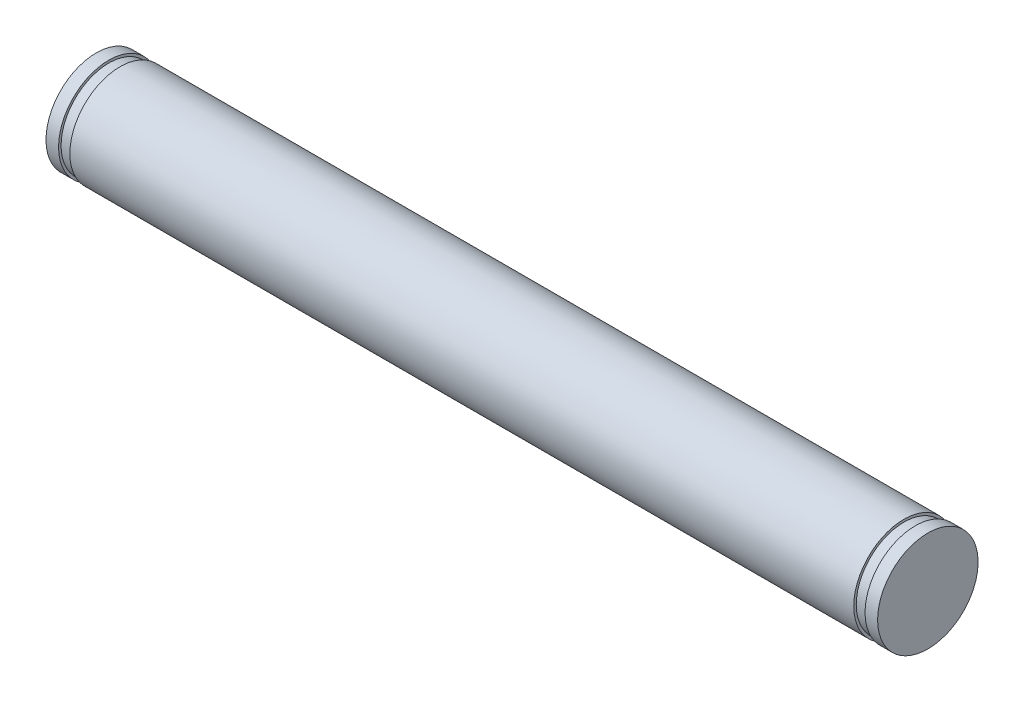
SolidWorks part; units mm, degrees
material "1060 Alloy"
ref_plane "Front Plane" through (0, 0, 0) normal (0, 0, 1) x (1, 0, 0)
ref_plane "Top Plane" through (0, 0, 0) normal (0, 1, 0) x (1, 0, 0)
ref_plane "Right Plane" through (0, 0, 0) normal (1, 0, 0) x (0, 0, -1)
sketch "Sketch1" plane through (0, 0, 0) normal (0, 0, 1) x (1, 0, 0)
  line L0 (62.4, 3.8) -> (63.3, 3.8)
  line L1 (0, 0) -> (62.4, 0)
  line L2 (0, 3.8) -> (0, 4)
  line L3 (0, 4) -> (62.4, 4)
  line L4 (62.4, 1.6806) -> (62.4, 1.7815)
  line L5 (63.3, 3.8) -> (63.3, 4)
  line L6 (63.3, 4) -> (64.3, 4)
  line L7 (64.3, 4) -> (64.3, 0)
  line L8 (62.4, 0) -> (64.3, 0)
  line L9 (62.4, 0) -> (64.3, 0)
  line L10 (62.1234, 1.7815) -> (62.4, 1.7815)
  line L11 (62.4, 1.6806) -> (62.1234, 1.7815)
  line L12 (62.4, 3.8) -> (62.4, 4)
  line L13 (0, 3.8) -> (-0.9, 3.8)
  line L14 (-0.9, 3.8) -> (-0.9, 4)
  line L15 (-0.9, 4) -> (-1.9, 4)
  line L16 (-1.9, 4) -> (-1.9, 0)
  line L17 (-1.9, 0) -> (0, 0)
  line L18 (-1.9, 0) -> (0, 0)
  dimension "D1" = 62.4
  dimension "D2" = 4
  dimension "D3" = 3.8
  dimension "D4" = 4
  dimension "D5" = 0.9
  dimension "D6" = 1
  dimension "D7" = 4
  dimension "D8" = 0.9
  dimension "D9" = 1
  dimension "D10" = 3.8
  dimension "D11" = 4
revolve "Revolve1" add sketch "Sketch1" angle 360 about L1
